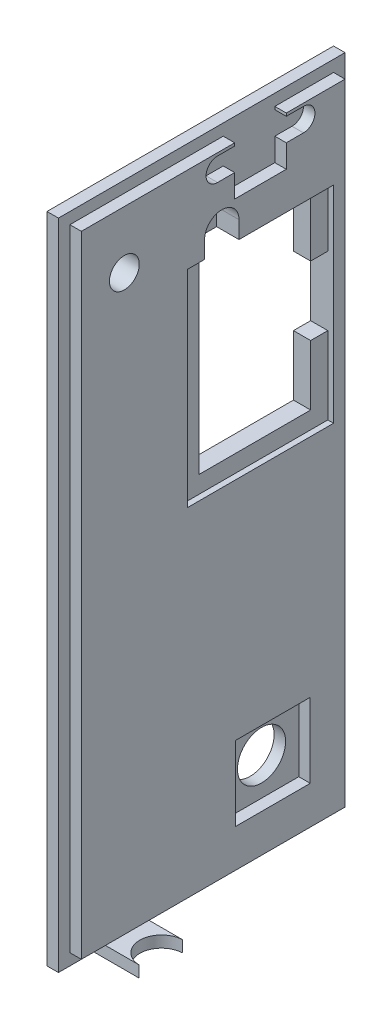
SolidWorks part; units mm, degrees
ref_plane "Ebene vorne" through (0, 0, 0) normal (0, 0, 1) x (1, 0, 0)
ref_plane "Ebene oben" through (0, 0, 0) normal (0, 1, 0) x (1, 0, 0)
ref_plane "Ebene rechts" through (0, 0, 0) normal (1, 0, 0) x (0, 0, -1)
sketch "Skizze1" plane through (0, 0, 0) normal (1, 0, 0) x (0, 0, -1)
  line L1 (-20.1266, 14.2405) -> (29.8734, 14.2405)
  line L2 (-20.1266, 14.2405) -> (-20.1266, -99.7595)
  line L3 (-20.1266, -99.7595) -> (29.8734, -99.7595)
  line L4 (29.8734, 14.2405) -> (29.8734, -99.7595)
  dimension "D1" = 50
  dimension "D2" = 114
extrude "Aufsatz-Linear austragen1" add sketch "Skizze1" along normal blind 2
sketch "Skizze2" plane through (2, 0, 0) normal (1, 0, 0) x (0, 0, -1)
  line L0 (-20.1266, 14.2405) -> (-20.1266, -99.7595) construction
  line L1 (-18.1266, 12.2405) -> (27.8734, 12.2405)
  line L2 (-18.1266, 12.2405) -> (-18.1266, -97.7595)
  line L3 (-18.1266, -97.7595) -> (27.8734, -97.7595)
  line L4 (27.8734, 12.2405) -> (27.8734, -97.7595)
  line L5 (29.8734, -99.7595) -> (29.8734, 14.2405) construction
  line L6 (29.8734, 14.2405) -> (-20.1266, 14.2405) construction
  line L7 (-20.1266, -99.7595) -> (29.8734, -99.7595) construction
  dimension "D1" = 2
  dimension "D2" = 2
  dimension "D3" = 2
  dimension "D4" = 2
extrude "Aufsatz-Linear austragen2" add sketch "Skizze2" along normal blind 2
sketch "Skizze3" plane through (4, 0, 0) normal (1, 0, 0) x (0, 0, -1)
  line L1 (27.8734, 12.2405) -> (-18.1266, 12.2405) construction
  line L2 (3.3734, -2.7595) -> (22.8734, -2.7595)
  line L3 (3.3734, -2.7595) -> (3.3734, -35.7595)
  line L4 (3.3734, -35.7595) -> (22.8734, -35.7595)
  line L5 (22.8734, -2.7595) -> (22.8734, -35.7595)
  line L6 (27.8734, -97.7595) -> (27.8734, 12.2405) construction
  dimension "D1" = 19.5
  dimension "D2" = 33
  dimension "D3" = 5
  dimension "D4" = 15
extrude "Schnitt-Linear austragen1" cut sketch "Skizze3" against normal up to next
sketch "Skizze4" plane through (4, 0, 0) normal (1, 0, 0) x (0, 0, -1)
  line L0 (22.8734, -2.7595) -> (3.3734, -2.7595) construction
  line L1 (0.3734, -2.7595) -> (25.8734, -2.7595)
  line L2 (0.3734, -2.7595) -> (0.3734, -35.7595)
  line L3 (0.3734, -35.7595) -> (25.8734, -35.7595)
  line L4 (25.8734, -2.7595) -> (25.8734, -35.7595)
  line L5 (3.3734, -35.7595) -> (22.8734, -35.7595) construction
  line L6 (3.3734, -2.7595) -> (22.8734, -2.7595) construction
  point P8 (13.1234, -2.7595)
  point P11 (13.1234, -2.7595)
  dimension "D1" = 25.5
  dimension "D2" = 0
extrude "Schnitt-Linear austragen2" cut sketch "Skizze4" against normal blind 1
sketch "Skizze5" plane through (4, 0, 0) normal (1, 0, 0) x (0, 0, -1)
  line L0 (3.3734, -35.7595) -> (3.3734, -2.7595) construction
  line L1 (3.3839, 0) -> (3.3734, -2.7595)
  line L3 (9.3734, 0.2505) -> (9.3734, -2.7595)
  line L4 (25.8734, -2.7595) -> (0.3734, -2.7595) construction
  circle A0 centre (6.3734, 0.2505) radius 3
  line M3 (0.3734, -2.7595) -> (25.8734, -2.7595)
  dimension "D1" = 6
  dimension "D2" = 3.01
  dimension "D3" = 3
extrude "Schnitt-Linear austragen3" cut sketch "Skizze5" against normal blind 3.9 contours A0 L1 L3 M3 | A0
sketch "Skizze6" plane through (3, 0, 0) normal (1, 0, 0) x (0, 0, -1)
  line L10 (22.8734, -2.7595) -> (22.8734, -35.7595) construction
  line L11 (22.8734, -13.2595) -> (25.8734, -13.2595)
  line L12 (22.8734, -13.2595) -> (22.8734, -25.2595)
  line L13 (22.8734, -25.2595) -> (25.8734, -25.2595)
  line L14 (25.8734, -13.2595) -> (25.8734, -25.2595)
  line L15 (25.8734, -35.7595) -> (25.8734, -2.7595) construction
  line L16 (22.8734, -35.7595) -> (25.8734, -35.7595) construction
  dimension "D1" = 10.5
  dimension "D2" = 12
extrude "Schnitt-Linear austragen4" cut sketch "Skizze6" against normal up to next
sketch "Skizze10" plane through (4, 0, 0) normal (1, 0, 0) x (0, 0, -1)
  line L0 (27.8734, 12.2405) -> (-18.1266, 12.2405) construction
  line L1 (8.6234, 12.2405) -> (17.6234, 12.2405)
  line L2 (8.6234, 12.2405) -> (8.6234, 8.2405)
  line L3 (8.6234, 8.2405) -> (17.6234, 8.2405)
  line L4 (17.6234, 12.2405) -> (17.6234, 8.2405)
  line L5 (0.3734, -35.7595) -> (25.8734, -35.7595) construction
  point P8 (13.1234, -35.7595)
  point P9 (13.1234, 8.2405)
  dimension "D1" = 9
  dimension "D2" = 4
extrude "Schnitt-Linear austragen5" cut sketch "Skizze10" against normal blind 2
sketch "Skizze11" plane through (4, 0, 0) normal (1, 0, 0) x (0, 0, -1)
  line L0 (8.6234, 12.2405) -> (8.6234, 8.2405) construction
  line L10 (29.8734, 14.2405) -> (-20.1266, 14.2405) construction
  line L11 (17.6234, 8.2405) -> (17.6234, 12.2405) construction
  circle A0 centre (20.6234, 9.7405) radius 2
  circle A1 centre (5.6234, 9.7405) radius 2
  dimension "D1" = 4
  dimension "D2" = 4.5
  dimension "D3" = 3
  dimension "D6" = 4
  dimension "D4" = 4.5
  dimension "D5" = 3
extrude "Schnitt-Linear austragen6" cut sketch "Skizze11" against normal blind 2
sketch "Skizze13" plane through (4, 0, 0) normal (1, 0, 0) x (0, 0, -1)
  line L0 (-18.1266, 12.2405) -> (-18.1266, -97.7595) construction
  line L1 (8.6234, 12.2405) -> (-18.1266, 12.2405) construction
  circle A0 centre (-10.6266, 2.2405) radius 2.6
  dimension "D1" = 5.2
  dimension "D3" = 10
  dimension "D2" = 7.5
extrude "Schnitt-Linear austragen7" cut sketch "Skizze13" against normal through all
sketch "Skizze14" plane through (2, 0, 0) normal (1, 0, 0) x (0, 0, -1)
  line L0 (-20.1266, -99.7595) -> (29.8734, -99.7595) construction
  line L5 (-13.9266, -99.7595) -> (-6.3266, -99.7595)
  line L6 (-13.9266, -99.7595) -> (-13.9266, -97.7595)
  line L7 (-13.9266, -97.7595) -> (-6.3266, -97.7595)
  line L8 (-6.3266, -99.7595) -> (-6.3266, -97.7595)
  line L9 (-18.1266, -97.7595) -> (27.8734, -97.7595) construction
  line L11 (-20.1266, 14.2405) -> (-20.1266, -99.7595) construction
  point P10 (-6.3266, -98.7595)
  dimension "D1" = 6.2
  dimension "D2" = 7.6
extrude "Aufsatz-Linear austragen3" add sketch "Skizze14" along normal blind 8
sketch "Skizze15" plane through (0, -99.7595, 0) normal (0, -1, 0) x (1, 0, 0)
  line L0 (10, 13.9266) -> (10, 6.3266) construction
  circle A0 centre (10, 10.1266) radius 3.8034
extrude "Schnitt-Linear austragen8" cut sketch "Skizze15" against normal up to next
sketch "Skizze16" plane through (4, 0, 0) normal (1, 0, 0) x (0, 0, -1)
  line L0 (25.8734, -35.7595) -> (25.8734, -25.2595) construction
  line L1 (0.3734, -35.7595) -> (25.8734, -35.7595)
  line L2 (0.3734, -35.7595) -> (0.3734, -38.7595)
  line L3 (0.3734, -38.7595) -> (25.8734, -38.7595)
  line L4 (25.8734, -35.7595) -> (25.8734, -38.7595)
  dimension "D1" = 3
sketch "Skizze18" plane through (4, 0, 0) normal (1, 0, 0) x (0, 0, -1)
extrude "Schnitt-Linear austragen10" cut sketch "Skizze16" against normal blind 1
sketch "Skizze17" plane through (4, 0, 0) normal (1, 0, 0) x (0, 0, -1)
sketch "Skizze21" plane through (4, 0, 0) normal (1, 0, 0) x (0, 0, -1)
  line L1 (8.8061, -78.1327) -> (21.8061, -78.1327)
  line L2 (8.8061, -78.1327) -> (8.8061, -91.1327)
  line L3 (8.8061, -91.1327) -> (21.8061, -91.1327)
  line L4 (21.8061, -78.1327) -> (21.8061, -91.1327)
  dimension "D1" = 13
  dimension "D2" = 13
extrude "Schnitt-Linear austragen11" cut sketch "Skizze21" against normal blind 2
sketch "Skizze22" plane through (2, 0, 0) normal (1, 0, 0) x (0, 0, -1)
  circle A0 centre (15.3061, -84.6327) radius 4.2
  point P2 (0, 0)
  point P4 (0, 0)
  dimension "D1" = 8.4
extrude "Schnitt-Linear austragen12" cut sketch "Skizze22" against normal up to next
sketch "Skizze23" plane through (4, 0, 0) normal (1, 0, 0) x (0, 0, -1)
  line L0 (5.6234, 11.7405) -> (8.6234, 11.7405)
  line L1 (8.6234, 12.2405) -> (8.6234, 8.2405) construction
  line L2 (5.6234, 7.7405) -> (8.6234, 7.7405)
  line L3 (8.6234, 12.2405) -> (8.6234, 8.2405) construction
  line L4 (20.6234, 11.7405) -> (17.6234, 11.7405)
  line L5 (17.6234, 8.2405) -> (17.6234, 12.2405) construction
  line L6 (20.6234, 7.7405) -> (17.6234, 7.7405)
  line L7 (8.6234, 11.7405) -> (8.6234, 7.7405)
  line L8 (5.6234, 11.7405) -> (5.6234, 7.7405)
  line L9 (20.6234, 11.7405) -> (20.6234, 7.7405)
  line L10 (17.6234, 11.7405) -> (17.6234, 7.7405)
  circle A0 centre (5.6234, 9.7405) radius 2 construction
  circle A1 centre (5.6234, 9.7405) radius 2 construction
  circle A2 centre (20.6234, 9.7405) radius 2 construction
  circle A3 centre (20.6234, 9.7405) radius 2 construction
  dimension "D1" = 3
extrude "Schnitt-Linear austragen13" cut sketch "Skizze23" against normal blind 2
sketch "Skizze26" plane through (4, 0, 0) normal (1, 0, 0) x (0, 0, -1)
  line L1 (8.6234, 8.2405) -> (17.6234, 8.2405)
  line L2 (8.6234, 8.2405) -> (8.6234, 3.7405)
  line L3 (8.6234, 3.7405) -> (17.6234, 3.7405)
  line L4 (17.6234, 8.2405) -> (17.6234, 3.7405)
  dimension "D1" = 4.5
extrude "Schnitt-Linear austragen18" cut sketch "Skizze26" against normal blind 2
